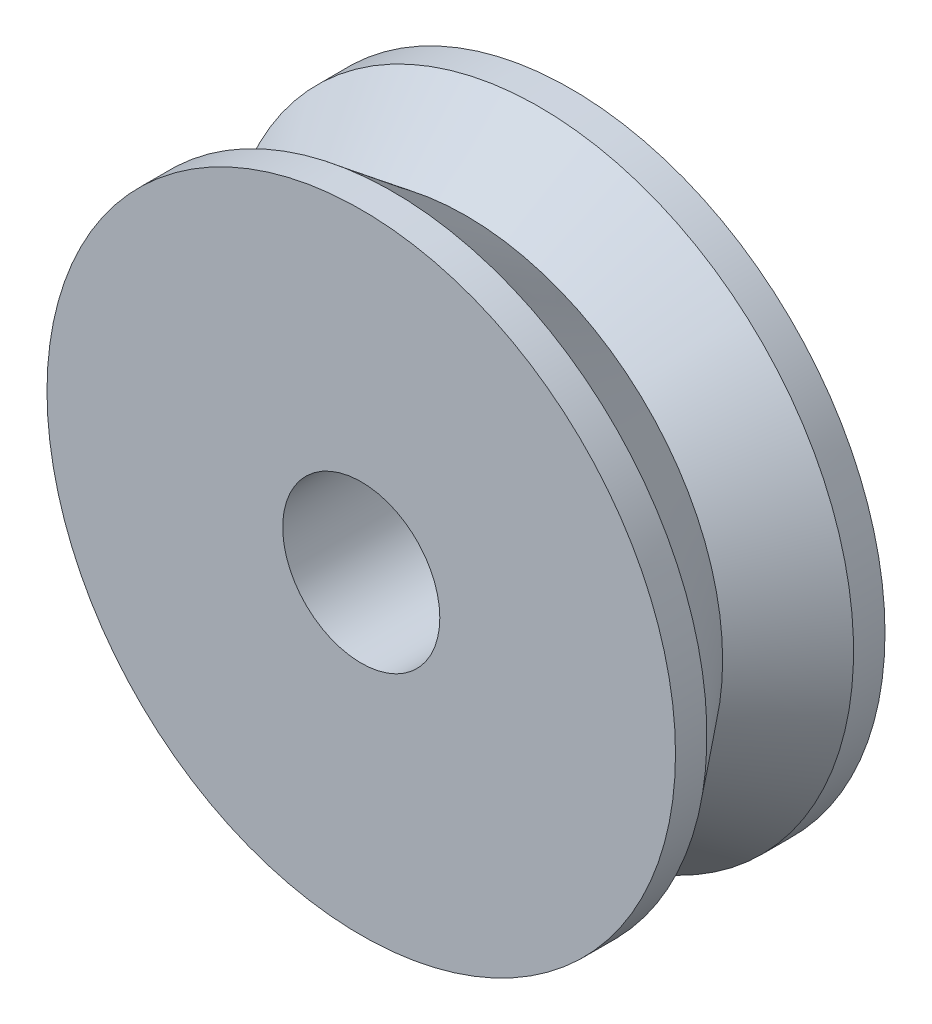
SolidWorks part; units mm, degrees
material "普通碳钢"
ref_plane "前视基准面" through (0, 0, 0) normal (0, 0, 1) x (1, 0, 0)
ref_plane "上视基准面" through (0, 0, 0) normal (0, 1, 0) x (1, 0, 0)
ref_plane "右视基准面" through (0, 0, 0) normal (1, 0, 0) x (0, 0, -1)
sketch "草图1" plane through (0, 0, 0) normal (0, 0, 1) x (1, 0, 0)
  circle A0 centre (0, 0) radius 6
  circle A1 centre (0, 0) radius 1.5
  dimension "D1" = 3
  dimension "D2" = 12
extrude "凸台-拉伸1" add sketch "草图1" along normal blind 4
sketch "草图2" plane through (0, 0, 0) normal (1, 0, 0) x (0, 0, -1)
  line L0 (0, 0) -> (-4.0094, 0) construction
  line L1 (-2, 6) -> (-2, 0) construction
  line L2 (0, 6) -> (-4, 6) construction
  line L3 (-3.4, 6) -> (-2, 4.9)
  line L4 (-0.6, 6) -> (-2, 4.9)
  line L5 (-3.4, 6) -> (-0.6, 6)
  dimension "D1" = 2.8
  dimension "D2" = 1.1
  dimension "D3" = 4.9
revolve "切除-旋转1" cut sketch "草图2" angle 360 about L0
